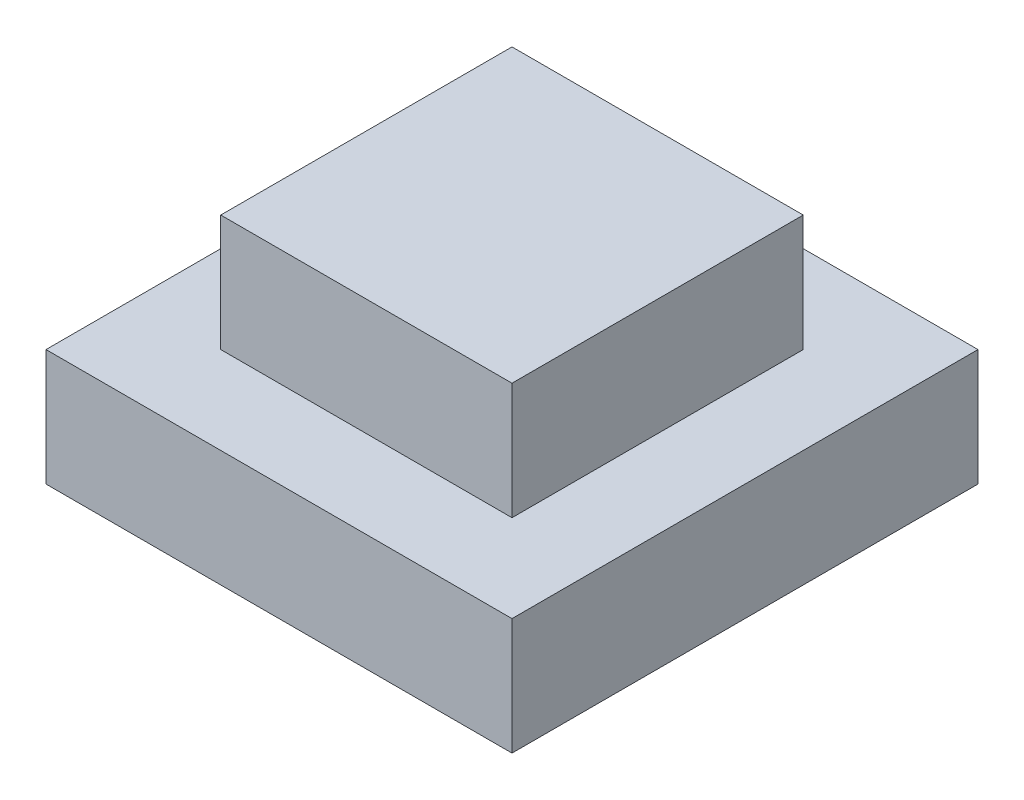
SolidWorks part; units mm, degrees
ref_plane "Plan de face" through (0, 0, 0) normal (0, 0, 1) x (1, 0, 0)
ref_plane "Plan de dessus" through (0, 0, 0) normal (0, 1, 0) x (1, 0, 0)
ref_plane "Plan de droite" through (0, 0, 0) normal (1, 0, 0) x (0, 0, -1)
sketch "Esquisse1" plane through (0, 0, 0) normal (0, 1, 0) x (1, 0, 0)
  line L1 (-4, 4) -> (4, 4)
  line L2 (-4, 4) -> (-4, -4)
  line L3 (-4, -4) -> (4, -4)
  line L4 (4, 4) -> (4, -4)
  line L5 (-4, 4) -> (4, -4) construction
  line L6 (-4, -4) -> (4, 4) construction
  point P0 (0, 0)
  dimension "D1" = 8
extrude "Boss.-Extru.1" add sketch "Esquisse1" along normal blind 3
chamfer "Chanfrein1" distance 1 angle 45 4 edges at (0, 0, -4) (-4, 0, 0) (0, 0, 4) (4, 0, 0)
sketch "Esquisse2" plane through (0, 3, 0) normal (0, 1, 0) x (1, 0, 0)
  line L0 (4, 4) -> (-4, 4) construction
  line L1 (-2.5, 2.5) -> (2.5, 2.5)
  line L2 (-2.5, 2.5) -> (-2.5, -2.5)
  line L3 (-2.5, -2.5) -> (2.5, -2.5)
  line L4 (2.5, 2.5) -> (2.5, -2.5)
  line L5 (-2.5, 2.5) -> (2.5, -2.5) construction
  line L6 (-2.5, -2.5) -> (2.5, 2.5) construction
  point P0 (0, 0)
  dimension "D1" = 1.5
extrude "Boss.-Extru.2" add sketch "Esquisse2" along normal blind 2
